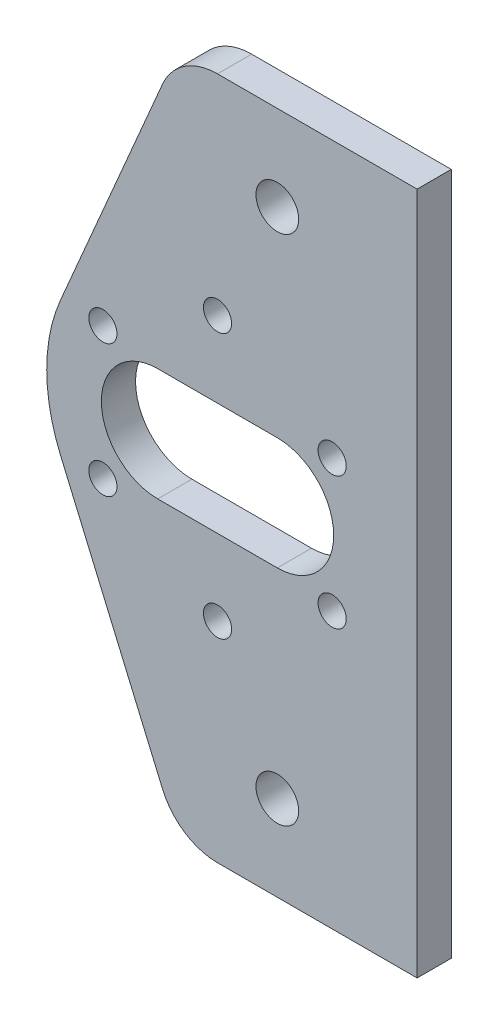
SolidWorks part; units mm, degrees
material "ABS"
ref_plane "Front Plane" through (0, 0, 0) normal (0, 0, 1) x (1, 0, 0)
ref_plane "Top Plane" through (0, 0, 0) normal (0, 1, 0) x (1, 0, 0)
ref_plane "Right Plane" through (0, 0, 0) normal (1, 0, 0) x (0, 0, -1)
sketch "Sketch1" plane through (0, 0, 0) normal (0, 0, 1) x (1, 0, 0)
  line L0 (0, -40) -> (0, 40)
  line L1 (-41.7527, -7.8788) -> (-29.804, -35.7576)
  line L3 (-23.37, -40) -> (0, -40)
  line L4 (-16.37, 30) -> (-16.37, 40) construction
  line L5 (-16.37, -30) -> (-16.37, -40) construction
  line L6 (-29.804, 35.7576) -> (-41.7527, 7.8788)
  line L8 (-23.37, 40) -> (0, 40)
  line L9 (-30.37, 0) -> (-16.37, 0) construction
  line L10 (-30.37, 6.6) -> (-16.37, 6.6)
  line L11 (-30.37, -6.6) -> (-16.37, -6.6)
  arc A0 (-41.7527, -7.8788) -> (-41.7527, 7.8788) centre (-23.37, 0) cw
  circle A2 centre (-16.37, 30) radius 2.5
  circle A3 centre (-16.37, -30) radius 2.5
  arc A5 (-29.804, -35.7576) -> (-23.37, -40) centre (-23.37, -33) ccw
  circle A7 centre (-23.37, 0) radius 15.5 construction
  circle A8 centre (-23.37, -15.5) radius 1.65
  circle A9 centre (-36.7934, -7.75) radius 1.65
  circle A10 centre (-36.7934, 7.75) radius 1.65
  arc A11 (-29.804, 35.7576) -> (-23.37, 40) centre (-23.37, 33) cw
  circle A12 centre (-23.37, 15.5) radius 1.65
  circle A13 centre (-9.9466, 7.75) radius 1.65
  circle A14 centre (-9.9466, -7.75) radius 1.65
  arc A15 (-30.37, 6.6) -> (-30.37, -6.6) centre (-30.37, 0) ccw
  arc A16 (-16.37, -6.6) -> (-16.37, 6.6) centre (-16.37, 0) ccw
  point P11 (0, 0)
  point P40 (-23.37, 0)
  point P41 (-23.37, 0)
  point P49 (-23.37, 0)
  point P53 (-23.37, 0)
  dimension "D5" = 6
  dimension "D6" = 20
  dimension "D8" = 5
  dimension "D9" = 23.37
  dimension "D13" = 7
  dimension "D3" = 3.3
  dimension "D4" = 31
  dimension "D2" = 14
  dimension "D7" = 80
  dimension "D10" = 13.2
  dimension "D11" = 10
  dimension "D12" = 16.37
  dimension "D14" = 23.37
extrude "Boss-Extrude1" add sketch "Sketch1" along normal mid plane 4
